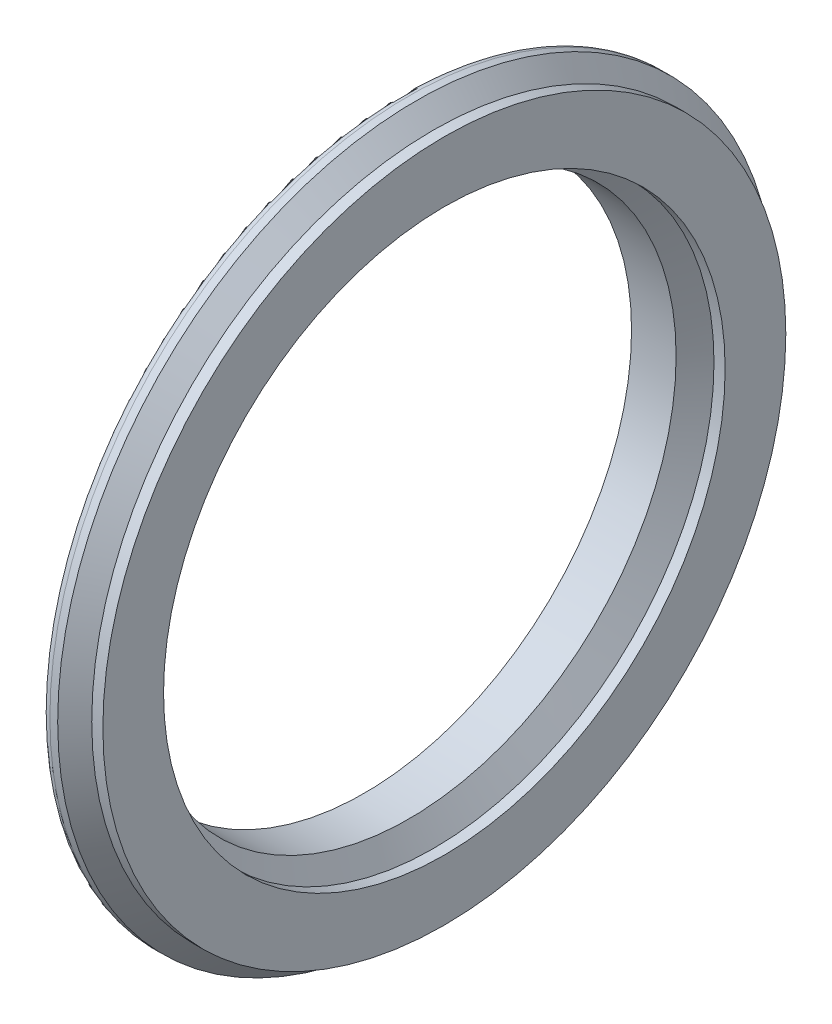
SolidWorks part; units mm, degrees
ref_plane "Front Plane" through (0, 0, 0) normal (0, 0, 1) x (1, 0, 0)
ref_plane "Top Plane" through (0, 0, 0) normal (0, 1, 0) x (1, 0, 0)
ref_plane "Right Plane" through (0, 0, 0) normal (1, 0, 0) x (0, 0, -1)
sketch "Sketch1" plane through (0, 0, 0) normal (0, 0, 1) x (1, 0, 0)
  line L0 (-1.25, 38.305) -> (-3.125, 40.25)
  line L1 (-3.125, 40.25) -> (-5, 40.25)
  line L2 (-5, 40.25) -> (-5, 36)
  line L3 (-5, 36) -> (-1.25, 36)
  line L4 (-1.25, 36) -> (-1.25, 34.59)
  line L5 (-1.25, 34.59) -> (-2.4837, 34.59)
  line L6 (-2.4837, 34.59) -> (-4.6609, 32.1018)
  line L7 (-4.6609, 32.1018) -> (-5, 33.18)
  line L8 (-5, 33.18) -> (-9, 33.18)
  line L9 (-9, 33.18) -> (-9, 30)
  line L10 (-9, 30) -> (-4, 30)
  line L11 (-4, 30) -> (-1.3429, 34.435)
  line L12 (-1.25, 34.4093) -> (-1.25, 31.5)
  line L13 (-1.25, 31.5) -> (0, 31.5)
  line L14 (0, 31.5) -> (0, 38.305)
  line L15 (0, 38.305) -> (-1.25, 38.305)
  line L16 (-9, 0) -> (0, 0) construction
  arc A0 (-1.3429, 34.435) -> (-1.25, 34.4093) centre (-1.3, 34.4093) cw
revolve "Revolve1" add sketch "Sketch1" angle 360 about L16
fillet "Fillet1" radius 1 1 edges at (-5, 0, -40.25)
